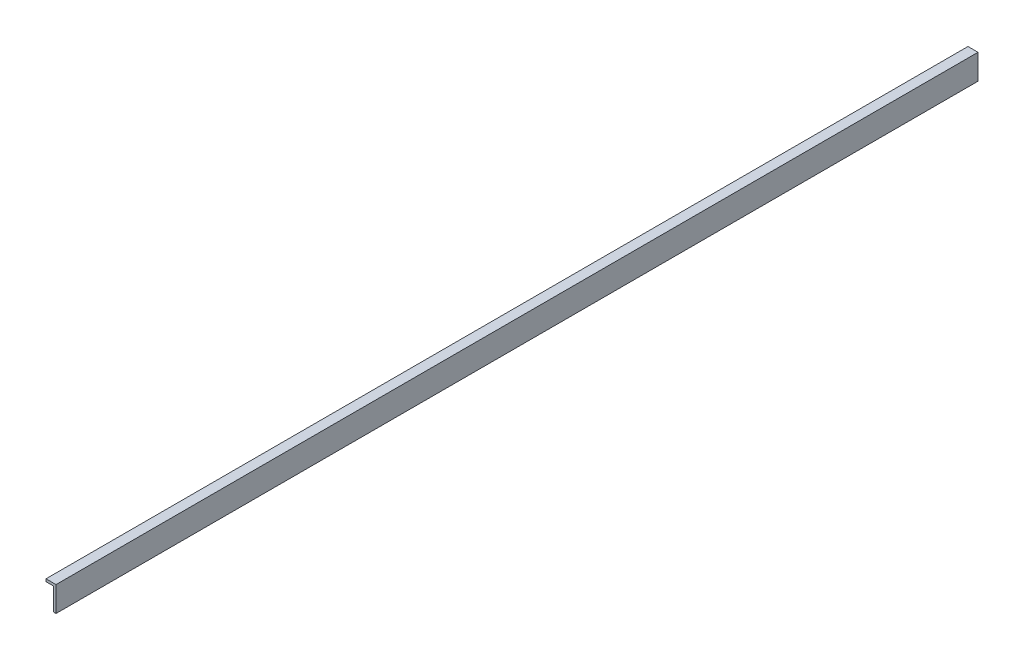
SolidWorks part; units mm, degrees
ref_plane "Front Plane" through (0, 0, 0) normal (0, 0, 1) x (1, 0, 0)
ref_plane "Top Plane" through (0, 0, 0) normal (0, 1, 0) x (1, 0, 0)
ref_plane "Right Plane" through (0, 0, 0) normal (1, 0, 0) x (0, 0, -1)
other "Configuration Table"
sketch "Sketch1" plane through (0, 0, 0) normal (0, 0, 1) x (1, 0, 0)
  line L0 (649.5, 404.5) -> (651.5, 404.5)
  line L1 (651.5, 404.5) -> (651.5, 424.5)
  line L2 (651.5, 424.5) -> (643.5, 424.5)
  line L3 (643.5, 424.5) -> (643.5, 422.5)
  line L4 (643.5, 422.5) -> (649.5, 422.5)
  line L5 (649.5, 422.5) -> (649.5, 404.5)
extrude "STORE_kaset_L_raf_4_sag_1" add sketch "Sketch1" against normal blind 735.5 from offset 20 separate body
